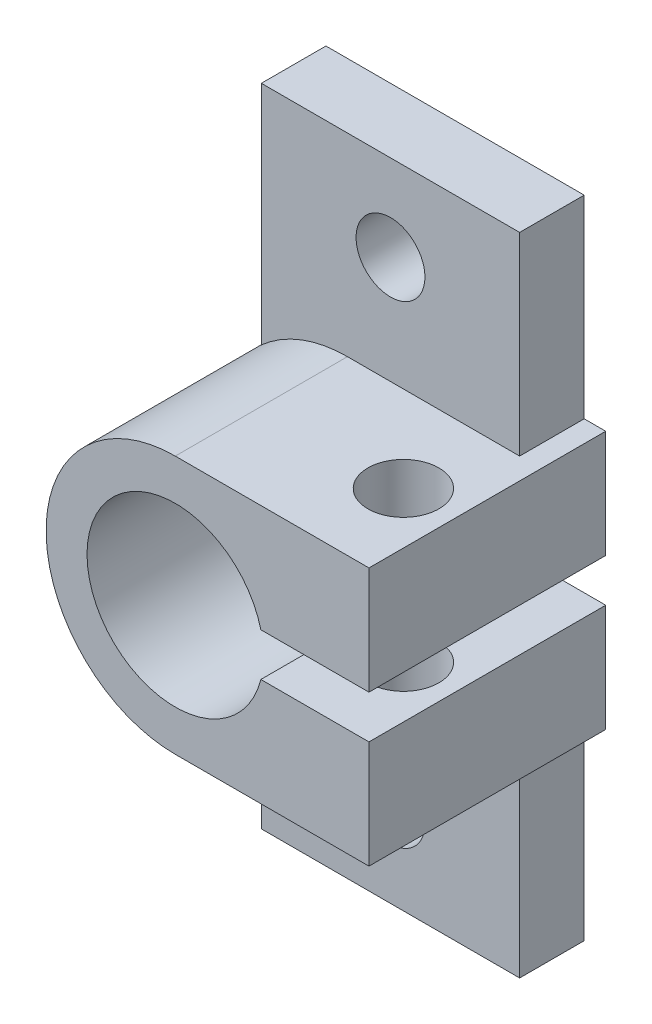
SolidWorks part; units mm, degrees
ref_plane "Plano frontal" through (0, 0, 0) normal (0, 0, 1) x (1, 0, 0)
ref_plane "Plano superior" through (0, 0, 0) normal (0, 1, 0) x (1, 0, 0)
ref_plane "Plano direito" through (0, 0, 0) normal (1, 0, 0) x (0, 0, -1)
sketch "Esboço1" plane through (0, 0, 0) normal (0, 0, 1) x (1, 0, 0)
  line L0 (-4, 15) -> (-4, 0.9)
  line L1 (8, -15) -> (8, -1)
  line L2 (0, 0) -> (8, 0) construction
  line L3 (3.9762, -1) -> (8, -1)
  line L4 (3.9762, 1) -> (8, 1)
  line L5 (0, 1) -> (8, 1) construction
  line L6 (0, -1) -> (8, -1) construction
  line L7 (8, 1) -> (8, 15)
  line L8 (-4, 15) -> (8, 15)
  line L9 (8, -15) -> (-4, -15)
  line L10 (-4, -0.9) -> (-4, -15)
  arc A0 (3.9762, 1) -> (-4, 0.9) centre (0, 0) ccw
  circle A1 centre (2, 11) radius 1.6
  circle A2 centre (2, -11) radius 1.6
  arc A3 (-4, -0.9) -> (3.9762, -1) centre (0, 0) ccw
  point P7 (2, 15)
  dimension "D1" = 12
  dimension "D2" = 3.2
  dimension "D3" = 8.2
  dimension "D4" = 30
  dimension "D7" = 22
  dimension "D8" = 4
  dimension "D5" = 1
  dimension "D6" = 1
extrude "Ressalto-extrusão1" add sketch "Esboço1" along normal blind 3 contours A3 L10 L9 L1 L3 A2 | A0 L4 L7 L8 L0 A1
sketch "Esboço2" plane through (0, 0, 3) normal (0, 0, 1) x (1, 0, 0)
  line L0 (9, 6) -> (9, 1)
  line L2 (9, 6) -> (0, 6)
  line L3 (9, -1) -> (9, -6)
  line L10 (9, -6) -> (0, -6)
  line L11 (0, 0) -> (11.2942, 0) construction
  line L12 (9, -1) -> (3.9762, -1)
  line L13 (3.9762, 1) -> (9, 1)
  arc A0 (0, -6) -> (0, 6) centre (0, 0) cw
  arc A1 (3.9762, 1) -> (-4, 0.9) centre (0, 0) ccw construction
  arc A8 (3.9762, 1) -> (3.9762, -1) centre (0, 0) ccw
  dimension "D2" = 6
  dimension "D3" = 9
  dimension "D4" = 2
extrude "Ressalto-extrusão2" add sketch "Esboço2" along normal blind 8 and the other way through all
sketch "Esboço3" plane through (0, 6, 0) normal (0, -1, 0) x (1, 0, 0)
  line L0 (4.2, 11) -> (4.2, 3) construction
  line L2 (-6, 3) -> (9, 3) construction
  line L3 (9, 0) -> (9, 11) construction
  line L5 (-6, 11) -> (-6, 0) construction
  line L6 (-4, 3) -> (8, 3) construction
  line L7 (9, 11) -> (0, 11) construction
  line L8 (9, 0) -> (9, 11) construction
  circle A0 centre (6.6, 7) radius 1.65
  point P13 (4.2, 7)
  dimension "D1" = 3.3
  dimension "D2" = 2.4
  dimension "D3" = 2.4
extrude "Corte-extrusão1" cut sketch "Esboço3" against normal through all both and the other way through all
